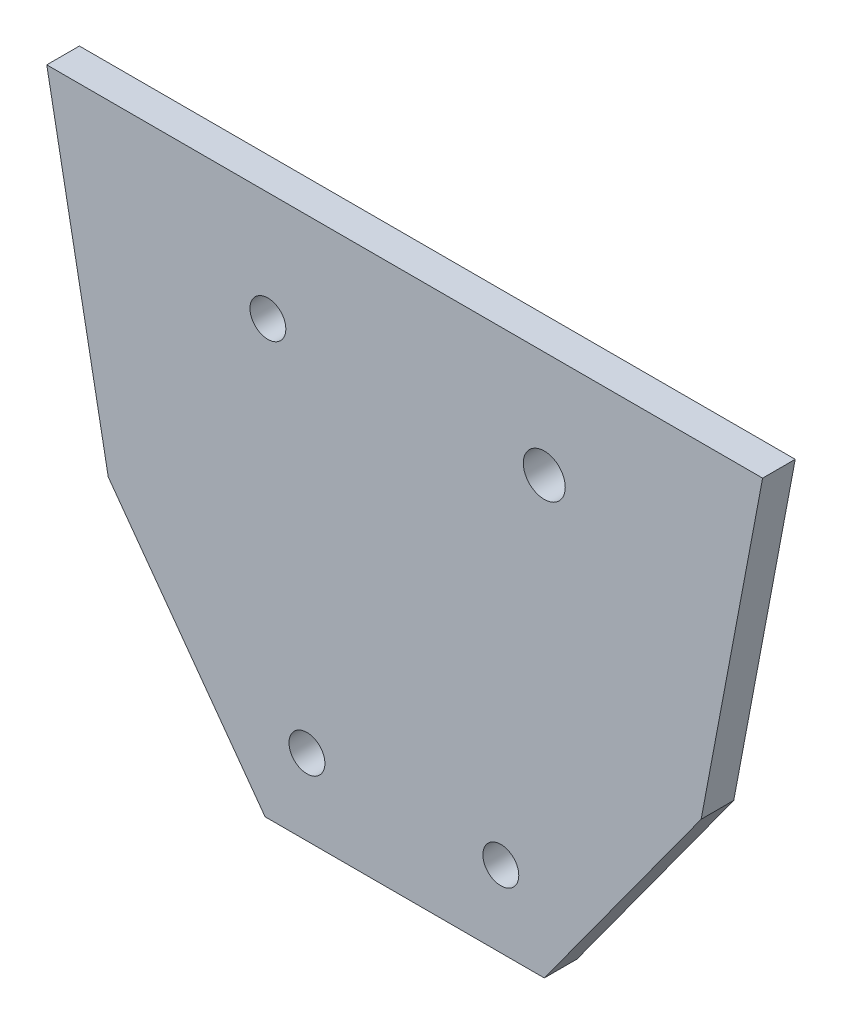
SolidWorks part; units mm, degrees
ref_plane "Front Plane" through (0, 0, 0) normal (0, 0, 1) x (1, 0, 0)
ref_plane "Top Plane" through (0, 0, 0) normal (0, 1, 0) x (1, 0, 0)
ref_plane "Right Plane" through (0, 0, 0) normal (1, 0, 0) x (0, 0, -1)
sketch "Sketch2" plane through (0, 0, 0) normal (0, 0, 1) x (1, 0, 0)
  line L3 (32.5684, 0) -> (-33.2722, -0.0003)
  line L5 (-13.1914, -49.8577) -> (12.4876, -49.8577)
  line L7 (12.4876, -49.8577) -> (26.915, -30)
  line L9 (26.915, -30) -> (32.5684, 0)
  line L10 (-13.1914, -49.8577) -> (-27.6188, -30)
  line L12 (-27.6188, -30) -> (-33.2722, -0.0003)
  circle A0 centre (-9.3427, -42.8602) radius 1.65
  circle A1 centre (8.4908, -42.8602) radius 1.65
  circle A2 centre (-12.934, -10.0504) radius 1.65
  circle A3 centre (12.4876, -9.8077) radius 1.9294
  dimension "D2" = 3.3
  dimension "D3" = 3.8588
  dimension "D4" = 3.3
  dimension "D5" = 3.3
extrude "Boss-Extrude1" add sketch "Sketch2" along normal blind 3
